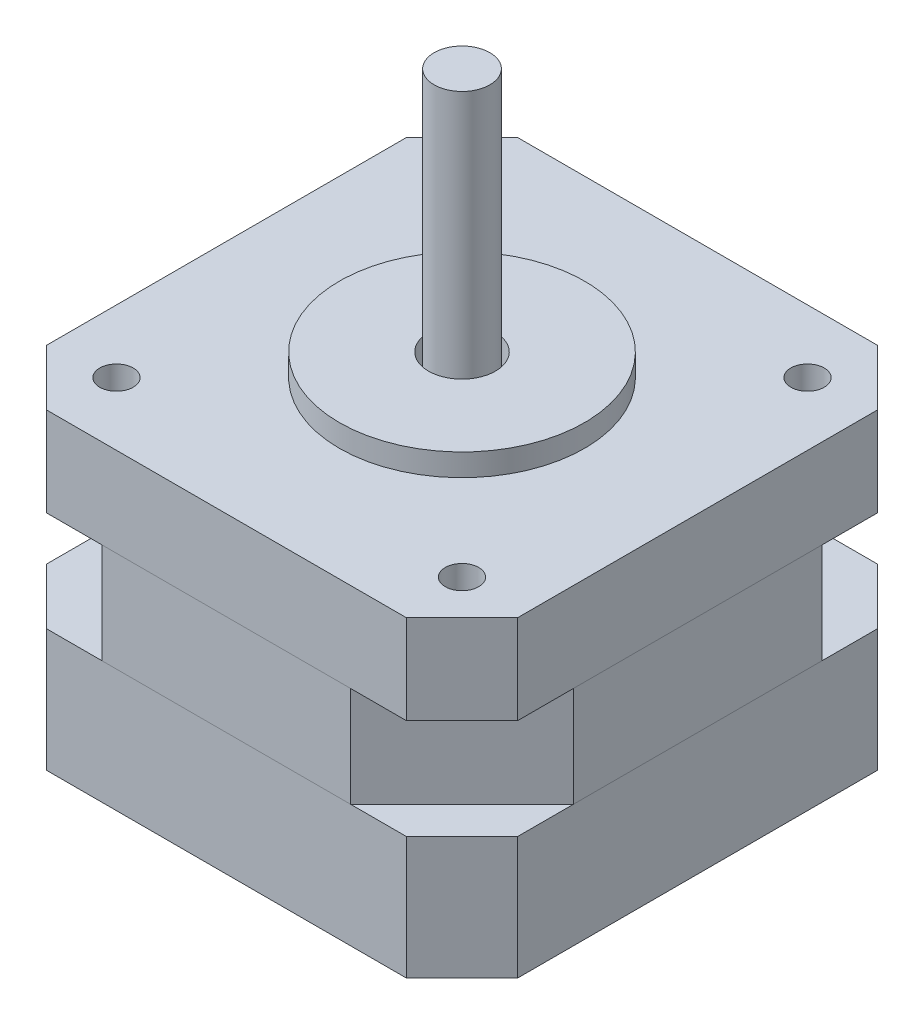
SolidWorks part; units mm, degrees
ref_plane "Front Plane" through (0, 0, 0) normal (0, 0, 1) x (1, 0, 0)
ref_plane "Top Plane" through (0, 0, 0) normal (0, 1, 0) x (1, 0, 0)
ref_plane "Right Plane" through (0, 0, 0) normal (1, 0, 0) x (0, 0, -1)
sketch "Sketch1" plane through (0, 0, 0) normal (0, 1, 0) x (1, 0, 0)
  line L0 (-21.15, -21.15) -> (21.15, 21.15) construction
  line L1 (-21.15, 21.15) -> (21.15, 21.15)
  line L2 (-21.15, 21.15) -> (-21.15, -21.15)
  line L3 (-21.15, -21.15) -> (21.15, -21.15)
  line L4 (21.15, 21.15) -> (21.15, -21.15)
  dimension "D1" = 42.3
extrude "Boss-Extrude1" add sketch "Sketch1" along normal blind 11
sketch "Sketch2" plane through (0, 11, 0) normal (0, 1, 0) x (1, 0, 0)
  line L1 (-21.15, 21.15) -> (21.15, 21.15)
  line L2 (-21.15, 21.15) -> (-21.15, -21.15)
  line L3 (-21.15, -21.15) -> (21.15, -21.15)
  line L4 (21.15, 21.15) -> (21.15, -21.15)
extrude "Boss-Extrude2" add sketch "Sketch2" along normal blind 9 separate body
sketch "Sketch3" plane through (0, 20, 0) normal (0, 1, 0) x (1, 0, 0)
  line L1 (-21.15, 21.15) -> (21.15, 21.15)
  line L2 (-21.15, 21.15) -> (-21.15, -21.15)
  line L3 (-21.15, -21.15) -> (21.15, -21.15)
  line L4 (21.15, 21.15) -> (21.15, -21.15)
extrude "Boss-Extrude3" add sketch "Sketch3" along normal blind 8 separate body
chamfer "Chamfer1" distance 10 angle 45 4 edges at (-21.15, 15.5, -21.15) (21.15, 15.5, -21.15) (21.15, 15.5, 21.15) (-21.15, 15.5, 21.15)
chamfer "Chamfer2" distance 5 angle 45 4 edges at (21.15, 24, -21.15) (-21.15, 24, -21.15) (-21.15, 24, 21.15) (21.15, 24, 21.15)
chamfer "Chamfer3" distance 5 angle 45 4 edges at (-21.15, 5.5, 21.15) (21.15, 5.5, 21.15) (21.15, 5.5, -21.15) (-21.15, 5.5, -21.15)
sketch "Sketch4" plane through (0, 28, 0) normal (0, 1, 0) x (1, 0, 0)
  circle A0 centre (0, 0) radius 11
  dimension "D1" = 22
extrude "Boss-Extrude4" add sketch "Sketch4" along normal blind 2
sketch "Sketch5" plane through (0, 30, 0) normal (0, 1, 0) x (1, 0, 0)
  circle A0 centre (0, 0) radius 3
  dimension "D1" = 6
extrude "Cut-Extrude1" cut sketch "Sketch5" against normal blind 4
sketch "Sketch6" plane through (0, 26, 0) normal (0, 1, 0) x (1, 0, 0)
  circle A0 centre (0, 0) radius 2.5
  dimension "D1" = 5
extrude "Boss-Extrude5" add sketch "Sketch6" along normal blind 26
sketch "Sketch7" plane through (0, 28, 0) normal (0, 1, 0) x (1, 0, 0)
  line L0 (15.5, 15.5) -> (-15.5, -15.5) construction
  line L1 (-15.5, 15.5) -> (15.5, 15.5) construction
  line L2 (-15.5, 15.5) -> (-15.5, -15.5) construction
  line L3 (-15.5, -15.5) -> (15.5, -15.5) construction
  line L4 (15.5, 15.5) -> (15.5, -15.5) construction
  circle A0 centre (-15.5, -15.5) radius 1.5
  circle A1 centre (-15.5, 15.5) radius 1.5
  circle A2 centre (15.5, 15.5) radius 1.5
  circle A3 centre (15.5, -15.5) radius 1.5
  dimension "D2" = 3
  dimension "D1" = 31
extrude "Cut-Extrude2" cut sketch "Sketch7" against normal blind 4.5
ref_plane "Plane1" through (0, 38, 0) normal (0, 1, 0) x (1, 0, 0)
sketch "Sketch8" plane through (0, 38, 0) normal (0, 1, 0) x (1, 0, 0)
  circle A0 centre (0, 0) radius 12.5
  dimension "D1" = 25
